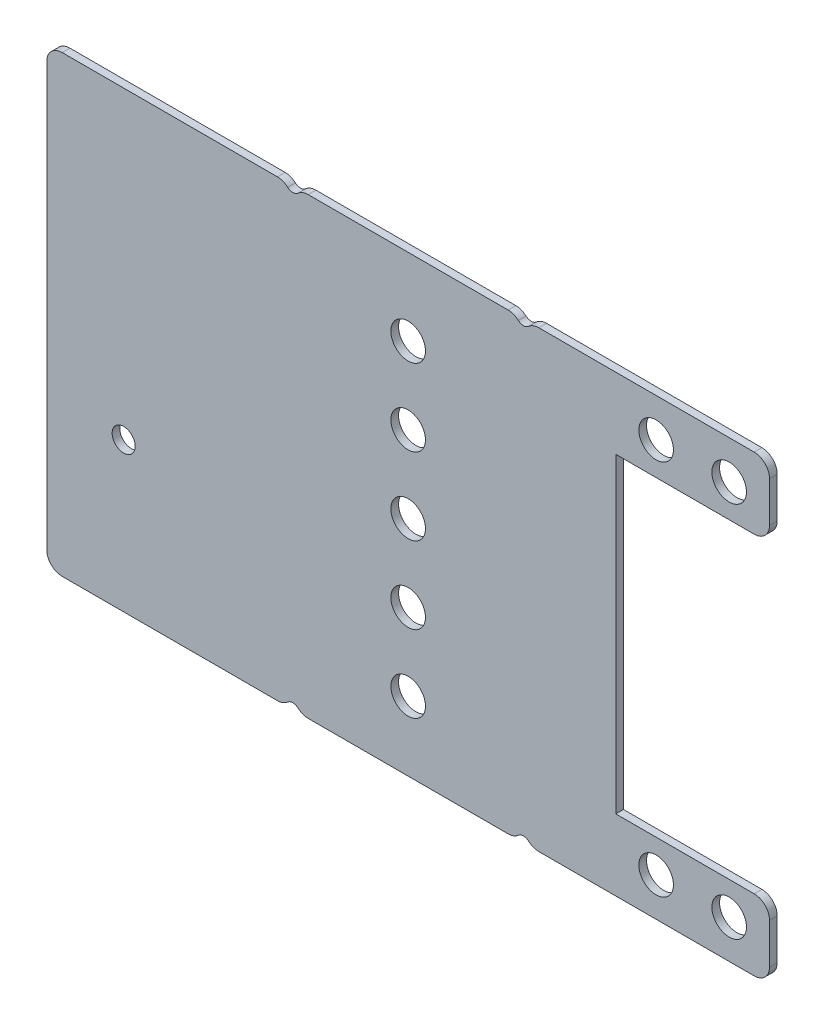
SolidWorks part; units mm, degrees
ref_plane "Front Plane" through (0, 0, 0) normal (0, 0, 1) x (1, 0, 0)
ref_plane "Top Plane" through (0, 0, 0) normal (0, 1, 0) x (1, 0, 0)
ref_plane "Right Plane" through (0, 0, 0) normal (1, 0, 0) x (0, 0, -1)
sketch "Sketch1" plane through (0, 0, 0) normal (0, 0, 1) x (1, 0, 0)
  line L0 (20, 42.5) -> (20, 47.75)
  line L1 (0, 0) -> (18, 0)
  line L2 (0, 0) -> (0, 40.5)
  line L3 (0, 40.5) -> (18, 40.5)
  line L4 (-14, 49.75) -> (-40, 49.75)
  line L5 (-74, 47.75) -> (-74, -7.25)
  line L6 (-40, -9.25) -> (-14, -9.25)
  line L7 (20, -7.25) -> (20, -2)
  line L8 (-12, -7.25) -> (-12, 47.75) construction
  line L9 (-42, -7.25) -> (-42, 47.75) construction
  line L10 (-72, 49.75) -> (-44, 49.75)
  line L11 (-72, -9.25) -> (-44, -9.25)
  line L12 (18, 49.75) -> (-10, 49.75)
  line L13 (18, -9.25) -> (-10, -9.25)
  line L14 (-64, -959.9377) -> (-64, 49040.0623) construction
  line L15 (-1052.4354, 10.14) -> (48947.5646, 10.14) construction
  circle A0 centre (5.25, 44.75) radius 2.25
  circle A1 centre (14.75, 44.75) radius 2.25
  circle A2 centre (14.75, -4.25) radius 2.25
  circle A3 centre (5.25, -4.25) radius 2.25
  arc A4 (-44, -9.25) -> (-42.6667, -8.7407) centre (-44, -7.25) ccw
  arc A5 (-42.6667, 49.2407) -> (-44, 49.75) centre (-44, 47.75) ccw
  arc A6 (-10, 49.75) -> (-11.3333, 49.2407) centre (-10, 47.75) ccw
  arc A7 (-11.3333, -8.7407) -> (-10, -9.25) centre (-10, -7.25) ccw
  arc A8 (-40, -9.25) -> (-41.3333, -8.7407) centre (-40, -7.25) cw
  arc A9 (-12.6667, 49.2407) -> (-14, 49.75) centre (-14, 47.75) ccw
  arc A10 (-14, -9.25) -> (-12.6667, -8.7407) centre (-14, -7.25) ccw
  arc A11 (-41.3333, 49.2407) -> (-40, 49.75) centre (-40, 47.75) cw
  arc A12 (18, 40.5) -> (20, 42.5) centre (18, 42.5) ccw
  arc A13 (20, 47.75) -> (18, 49.75) centre (18, 47.75) ccw
  arc A14 (18, 0) -> (20, -2) centre (18, -2) cw
  arc A15 (20, -7.25) -> (18, -9.25) centre (18, -7.25) cw
  arc A16 (-72, -9.25) -> (-74, -7.25) centre (-72, -7.25) cw
  arc A17 (-72, 49.75) -> (-74, 47.75) centre (-72, 47.75) ccw
  circle A18 centre (-27, 39.75) radius 2.25
  circle A19 centre (-27, 29.75) radius 2.25
  circle A20 centre (-27, 19.75) radius 2.25
  circle A21 centre (-27, 9.7494) radius 2.25
  circle A22 centre (-27, -0.2506) radius 2.25
  circle A23 centre (-64, 10.14) radius 1.5
  arc A24 (-11.3333, -8.7407) -> (-12.6667, -8.7407) centre (-12, -9.4861) ccw
  arc A25 (-41.3333, -8.7407) -> (-42.6667, -8.7407) centre (-42, -9.4861) ccw
  arc A26 (-12.6667, 49.2407) -> (-11.3333, 49.2407) centre (-12, 49.9861) ccw
  arc A27 (-41.3333, 49.2407) -> (-42.6667, 49.2407) centre (-42, 49.9861) cw
  dimension "D6" = 4.5
  dimension "D7" = 4.5
  dimension "D8" = 4.5
  dimension "D9" = 4.5
  dimension "D21" = 2
  dimension "D22" = 2
  dimension "D23" = 2
  dimension "D24" = 10.14
  dimension "D25" = 2
  dimension "D26" = 15
  dimension "D29" = 4.5
  dimension "D30" = 4.5
  dimension "D34" = 4.5
  dimension "D37" = 4.5
  dimension "D38" = 10
  dimension "D40" = 4.5
  dimension "D41" = 10
  dimension "D42" = 3
  dimension "D43" = 1
  dimension "D1" = 40.5
  dimension "D2" = 20
  dimension "D3" = 20
  dimension "D4" = 9.5
  dimension "D5" = 9.5
  dimension "D10" = 4.25
  dimension "D11" = 4.25
  dimension "D12" = 5.25
  dimension "D13" = 5.25
  dimension "D14" = 5.25
  dimension "D15" = 5.25
  dimension "D16" = 5
  dimension "D17" = 5
  dimension "D18" = 12
  dimension "D19" = 32
  dimension "D20" = 30
  dimension "D27" = 15
  dimension "D28" = 10
  dimension "D31" = 10
  dimension "D32" = 15
  dimension "D33" = 10
  dimension "D35" = 15
  dimension "D36" = 10.0006
  dimension "D39" = 15
extrude "Boss-Extrude1" add sketch "Sketch1" along normal blind 1
